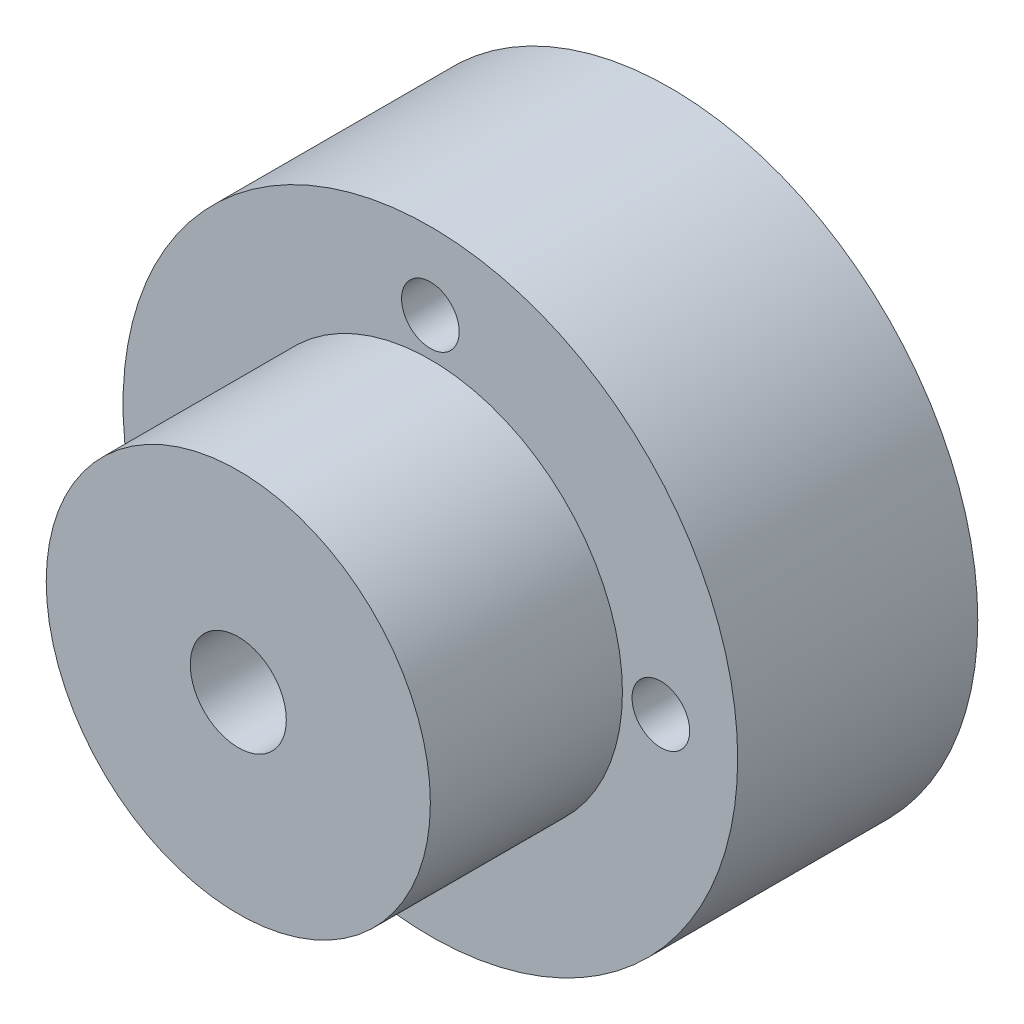
SolidWorks part; units mm, degrees
ref_plane "前视基准面" through (0, 0, 0) normal (0, 0, 1) x (1, 0, 0)
ref_plane "上视基准面" through (0, 0, 0) normal (0, 1, 0) x (1, 0, 0)
ref_plane "右视基准面" through (0, 0, 0) normal (1, 0, 0) x (0, 0, -1)
other "Configuration Table"
sketch "草图1" plane through (0, 0, 0) normal (0, 0, 1) x (1, 0, 0)
  circle A0 centre (0, 0) radius 16
extrude "凸台-拉伸1" add sketch "草图1" along normal blind 12.5
sketch "草图2" plane through (0, 0, 12.5) normal (0, 0, 1) x (1, 0, 0)
  circle A0 centre (0, 0) radius 10
extrude "凸台-拉伸2" add sketch "草图2" along normal blind 10
sketch "草图3" plane through (0, 0, 22.5) normal (0, 0, 1) x (1, 0, 0)
  circle A0 centre (0, 0) radius 2.5
extrude "切除-拉伸1" cut sketch "草图3" against normal through all
sketch "草图4" plane through (0, 0, 0) normal (0, 0, -1) x (-1, 0, 0)
  circle A1 centre (0, 12) radius 1.5
  circle A2 centre (12, 0) radius 1.5
  circle A3 centre (0, -12) radius 1.5
  circle A4 centre (-12, 0) radius 1.5
extrude "切除-拉伸2" cut sketch "草图4" against normal through all
